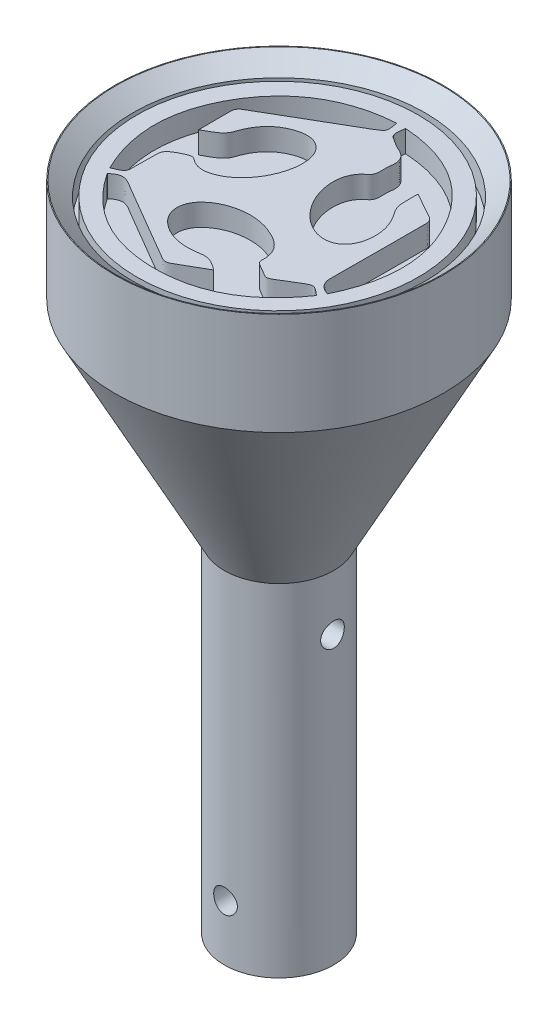
SolidWorks part; units mm, degrees
ref_plane "Piano frontale" through (0, 0, 0) normal (0, 0, 1) x (1, 0, 0)
ref_plane "Piano superiore" through (0, 0, 0) normal (0, 1, 0) x (1, 0, 0)
ref_plane "Piano destro" through (0, 0, 0) normal (1, 0, 0) x (0, 0, -1)
ref_plane "Piano1" through (0, 0, 0) normal (0, 0, -1) x (-1, 0, 0)
sketch "Schizzo1" plane through (0, 0, 0) normal (0, 0, -1) x (-1, 0, 0)
  line L0 (-22.5, 0) -> (0, 0)
  line L1 (0, 0) -> (0, 14.04)
  line L2 (0, 14.04) -> (-22.5, 14.04)
  line L3 (-22.5, 14.04) -> (-22.5, 0)
  line L4 (0, 0) -> (0, 14.04) construction
  line L5 (0, 19.9908) -> (0, -13.2342) construction
  dimension "D1" = 14.04
  dimension "D2" = 22.5
revolve "Rivoluzione1" add sketch "Schizzo1" angle 360 about L4
hole_wizard "Preforo Helicoil M39-1" positions "Schizzo3" profile "Schizzo2" hole size "M39x3.0" standard "Ansi Metric"
sketch "Schizzo3" plane through (0, 14.04, 0) normal (0, 1, 0) x (1, 0, 0)
  point P0 (0, 0)
sketch "Schizzo2" plane through (0, 14.04, 0) normal (1, 0, 0) x (0, 0, 1)
  line L0 (0, 0) -> (0, 5)
  line L1 (0, 5) -> (20, 5)
  line L2 (20, 5) -> (20, 2)
  line L3 (20, 2) -> (22.3835, 0)
  line L5 (22.3835, 0) -> (0, 0)
  line L6 (-20, 2) -> (-22.3835, 0) construction
  line L10 (0, 5) -> (-20, 5) construction
  line L11 (0, -6.35) -> (0, 107.95) construction
  dimension "Hole Dia." = 40
  dimension "Hole Depth" = 5
  dimension "Near C'Sink Dia." = 44.767
  dimension "Near C'Sink Angle" = 100
  dimension "Drill Angle" = 180
ref_plane "Piano2" through (0, 19, 0) normal (0, -1, 0) x (0, 0, 1)
sketch "Schizzo4" plane through (0, 19, 0) normal (0, -1, 0) x (0, 0, 1)
  circle A0 centre (-0.0209, 0.2088) radius 19.2566
extrude "Estrusione-Estrusione1" add sketch "Schizzo4" against normal blind 3 from surface at 9.96 starting at face at (0, 9.04, 20)
ref_plane "Piano3" through (0, 4.0001, 0) normal (0, 1, 0) x (1, 0, 0)
sketch "Schizzo5" plane through (0, 4.0001, 0) normal (0, 1, 0) x (1, 0, 0)
  arc A0 (-14.499, -9.0522) -> (-14.5293, -9.0002) centre (-13.9443, -8.6934) cw
  spline S0 degree 3 poles (-14.5293, -9.0002) (-14.5296, -8.9992) (-14.5303, -8.997) (-14.5301, -8.9936) (-14.53, -8.9903) (-14.5298, -8.987) (-14.5297, -8.9836) (-14.5296, -8.9803) (-14.5296, -8.977) (-14.5296, -8.9747) (-14.5296, -8.9736) knots 0 0 0 0 0.124119 0.24919 0.374331 0.499471 0.624605 0.749737 0.87487 1 1 1 1
  spline S1 degree 3 poles (-14.5296, -8.9736) (-14.4091, -8.8663) (-14.1681, -8.6517) (-13.7482, -8.4021) (-13.2752, -8.2701) (-12.782, -8.2936) (-12.3249, -8.4665) (-11.8982, -8.698) (-11.4855, -8.9555) (-11.0671, -9.2052) (-10.6494, -9.4559) (-10.2308, -9.7053) (-9.8118, -9.9539) (-9.3924, -10.2018) (-8.9725, -10.449) (-8.5523, -10.6956) (-8.1318, -10.9417) (-7.711, -11.1872) (-7.2899, -11.4324) (-6.8686, -11.6771) (-6.4472, -11.9216) (-6.0256, -12.1658) (-5.6039, -12.4099) (-5.1821, -12.6538) (-4.7604, -12.8977) (-4.3386, -13.1416) (-3.9168, -13.3856) (-3.4952, -13.6297) (-3.0737, -13.874) (-2.6523, -14.1186) (-2.2311, -14.3635) (-1.8102, -14.6089) (-1.3904, -14.8562) (-0.9688, -15.1) (-0.5569, -15.3548) (-0.0689, -15.4804) (0.4053, -15.3186) (0.8078, -15.0542) (1.2262, -14.8098) (1.6436, -14.5652) (2.0636, -14.3248) (2.4846, -14.0862) (2.9064, -13.8491) (3.3284, -13.6122) (3.7501, -13.375) (4.0305, -13.2155) (4.1707, -13.1358) knots 0 0 0 0 0.022617 0.045226 0.067918 0.090547 0.113217 0.135873 0.158666 0.181458 0.204249 0.227041 0.249832 0.272624 0.295415 0.318207 0.340998 0.36379 0.386582 0.409374 0.432166 0.454958 0.47775 0.500542 0.523334 0.546125 0.568917 0.591709 0.614501 0.637293 0.660084 0.682876 0.705668 0.72846 0.751198 0.773726 0.796268 0.818905 0.841546 0.864184 0.88682 0.909456 0.932092 0.954728 0.977364 1 1 1 1
  spline S2 degree 3 poles (4.1557, -13.1089) (4.1567, -13.1098) (4.1586, -13.1115) (4.1606, -13.1149) (4.1623, -13.1183) (4.1639, -13.1218) (4.1655, -13.1254) (4.1672, -13.1289) (4.1689, -13.1324) (4.1701, -13.1346) (4.1707, -13.1358) knots 0 0 0 0 0.124255 0.24931 0.374365 0.499494 0.624631 0.749743 0.874847 1 1 1 1
  spline S3 degree 3 poles (4.1557, -13.1089) (4.0758, -13.0505) (3.916, -12.9337) (3.6748, -12.7607) (3.4286, -12.5946) (3.1753, -12.4397) (2.9134, -12.3007) (2.6391, -12.1882) (2.3534, -12.1085) (2.0607, -12.0627) (1.7649, -12.0521) (1.4693, -12.0758) (1.1773, -12.1307) (0.8837, -12.1774) (0.5893, -12.2128) (0.295, -12.2384) (0.0007, -12.2535) (-0.2936, -12.2578) (-0.588, -12.2511) (-0.8825, -12.2328) (-1.177, -12.2027) (-1.4715, -12.1602) (-1.7651, -12.1047) (-2.0562, -12.036) (-2.3431, -11.954) (-2.6248, -11.8584) (-2.9011, -11.7494) (-3.172, -11.6266) (-3.4374, -11.4899) (-3.6964, -11.3394) (-3.9477, -11.1761) (-4.1902, -11.001) (-4.4235, -10.8147) (-4.6484, -10.6177) (-4.8598, -10.4046) (-5.0536, -10.1751) (-5.2273, -9.9306) (-5.3783, -9.6716) (-5.505, -9.3992) (-5.6056, -9.1162) (-5.6805, -8.8259) (-5.7285, -8.5299) (-5.7463, -8.2299) (-5.7328, -7.9298) (-5.6872, -7.6335) (-5.6109, -7.3431) (-5.5056, -7.0612) (-5.3743, -6.7899) (-5.2213, -6.5305) (-5.0478, -6.2844) (-4.8537, -6.0549) (-4.6429, -5.8413) (-4.4176, -5.6426) (-4.1813, -5.4572) (-3.9372, -5.2832) (-3.6863, -5.1213) (-3.4287, -4.9716) (-3.1644, -4.8341) (-2.8936, -4.7087) (-2.6162, -4.5955) (-2.3335, -4.4946) (-2.0469, -4.4063) (-1.7579, -4.3305) (-1.4669, -4.2669) (-1.1746, -4.2126) (-0.8806, -4.1683) (-0.5849, -4.1341) (-0.2873, -4.1105) (0.0119, -4.0979) (0.3117, -4.0965) (0.6109, -4.1065) (0.9087, -4.1282) (1.2045, -4.1611) (1.4984, -4.2052) (1.7904, -4.2604) (2.0803, -4.3266) (2.3681, -4.4036) (2.6539, -4.4914) (2.9369, -4.5896) (3.2164, -4.6974) (3.4914, -4.814) (3.7619, -4.9388) (4.0282, -5.0713) (4.2898, -5.2123) (4.5455, -5.3643) (4.7943, -5.5295) (5.0349, -5.7098) (5.2634, -5.9076) (5.4762, -6.1226) (5.6704, -6.3543) (5.8431, -6.6031) (5.9915, -6.8672) (6.1126, -7.1441) (6.2058, -7.4312) (6.2709, -7.7269) (6.3095, -8.0281) (6.3214, -8.3323) (6.3143, -8.6336) (6.3219, -8.9416) (6.4961, -9.2103) (6.7648, -9.3586) (7.0193, -9.5262) (7.2804, -9.6858) (7.5422, -9.8438) (7.8061, -9.9975) (8.0729, -10.1491) (8.3394, -10.2904) (8.6187, -10.4501) (8.9347, -10.3695) (9.2138, -10.2462) (9.4757, -10.0802) (9.7402, -9.923) (10.0034, -9.7627) (10.2667, -9.6028) (10.5298, -9.4424) (10.7929, -9.2821) (11.056, -9.1218) (11.3193, -8.9618) (11.5825, -8.8016) (11.847, -8.6437) (12.1105, -8.4843) (12.3848, -8.3456) (12.67, -8.225) (12.9912, -8.218) (13.1784, -8.3092) (13.2722, -8.3549) knots 0 0 0 0 0.008034 0.016066 0.024094 0.032131 0.040157 0.048136 0.056147 0.064169 0.072134 0.080116 0.08818 0.096235 0.10425 0.112237 0.120206 0.128165 0.136127 0.144102 0.152104 0.160152 0.168245 0.176346 0.184419 0.192454 0.200481 0.208519 0.216588 0.224706 0.232821 0.240902 0.248971 0.257047 0.265162 0.273305 0.2814 0.289478 0.297605 0.305745 0.313826 0.321906 0.330046 0.338175 0.34624 0.35434 0.362498 0.37063 0.378767 0.386921 0.39504 0.403136 0.411261 0.419402 0.427509 0.43558 0.443631 0.451682 0.459748 0.467849 0.47599 0.484107 0.492183 0.500234 0.508274 0.516313 0.52436 0.532431 0.540538 0.548658 0.556762 0.564834 0.572882 0.580918 0.588951 0.596991 0.605049 0.613133 0.621251 0.62936 0.637438 0.645494 0.653537 0.661572 0.669612 0.677676 0.685798 0.694 0.70218 0.710328 0.718508 0.726726 0.734875 0.743003 0.751188 0.759415 0.767621 0.775838 0.784009 0.792122 0.800376 0.808647 0.81692 0.825192 0.833464 0.841736 0.850004 0.858279 0.866593 0.874961 0.883297 0.891632 0.899968 0.908304 0.91664 0.924976 0.933312 0.941648 0.949984 0.95832 0.966656 0.974957 0.983279 0.991625 1 1 1 1
  spline S4 degree 3 poles (13.2722, -8.3549) (13.388, -8.4303) (13.62, -8.5811) (13.9371, -8.8499) (14.1486, -9.0284) (14.2545, -9.1177) knots 0 0 0 0 0.332682 0.666132 1 1 1 1
  spline S5 degree 3 poles (14.2545, -9.1177) (14.0751, -9.3707) (13.7168, -9.8757) (13.1489, -10.6091) (12.5516, -11.3159) (11.9228, -11.994) (11.2607, -12.6419) (10.564, -13.2573) (9.8348, -13.8352) (9.0763, -14.3698) (8.2925, -14.8573) (7.4839, -15.2967) (6.6502, -15.6874) (5.7912, -16.029) (4.9088, -16.3202) (4.0091, -16.5597) (3.0983, -16.7458) (2.1815, -16.8805) (1.2591, -16.9675) (0.3313, -17.0087) (-0.5993, -17.0045) (-1.5281, -16.9577) (-2.4505, -16.8661) (-3.3641, -16.7277) (-4.2688, -16.5403) (-5.1639, -16.3017) (-6.0473, -16.0107) (-6.9128, -15.6676) (-7.7537, -15.2745) (-8.5658, -14.8339) (-9.3491, -14.3467) (-10.104, -13.8139) (-10.8307, -13.2365) (-11.5268, -12.6178) (-12.1898, -11.9633) (-12.8179, -11.2775) (-13.4113, -10.5627) (-13.9747, -9.8223) (-14.324, -9.3092) (-14.499, -9.0522) knots 0 0 0 0 0.027124 0.054151 0.081105 0.108038 0.13501 0.162094 0.189308 0.216347 0.243214 0.269999 0.296795 0.323697 0.350803 0.378025 0.405083 0.432061 0.459039 0.486086 0.513259 0.540405 0.567396 0.594301 0.62119 0.64816 0.67528 0.702504 0.729535 0.756425 0.783272 0.810167 0.837198 0.864415 0.89158 0.918655 0.945713 0.972812 1 1 1 1
extrude "Taglio-Estrusione1" cut sketch "Schizzo5" against normal blind 3 from surface at 8.0399 starting at face at (-0.2088, 12.04, -19.2775)
ref_plane "Piano4" through (0, 4.0015, 0) normal (0, 1, 0) x (1, 0, 0)
sketch "Schizzo6" plane through (0, 4.0015, 0) normal (0, 1, 0) x (1, 0, 0)
  spline S0 degree 3 poles (9.1765, 9.8298) (9.1767, 9.8311) (9.1771, 9.8338) (9.179, 9.8374) (9.1811, 9.8409) (9.1833, 9.8442) (9.1856, 9.8476) (9.1878, 9.851) (9.1899, 9.8545) (9.1912, 9.8568) (9.1919, 9.858) knots 0 0 0 0 0.12437 0.249211 0.374335 0.499487 0.62465 0.749768 0.874894 1 1 1 1
  spline S1 degree 3 poles (9.1765, 9.8298) (9.1756, 9.7199) (9.1737, 9.5) (9.1712, 9.1702) (9.1687, 8.8403) (9.166, 8.5105) (9.163, 8.181) (9.1693, 7.8522) (9.1932, 7.5246) (9.2445, 7.1995) (9.3297, 6.8809) (9.4515, 6.5751) (9.6053, 6.2851) (9.7943, 6.0178) (9.9859, 5.7529) (10.1622, 5.4786) (10.3278, 5.1994) (10.4806, 4.9144) (10.6205, 4.6236) (10.7473, 4.3268) (10.8603, 4.0238) (10.9589, 3.7142) (11.0415, 3.3988) (11.1074, 3.0797) (11.1554, 2.759) (11.1857, 2.4378) (11.1982, 2.116) (11.1928, 1.7937) (11.1709, 1.4709) (11.1345, 1.1478) (11.0805, 0.8264) (11.0062, 0.5091) (10.9096, 0.1982) (10.7887, -0.1048) (10.643, -0.3971) (10.4718, -0.675) (10.2729, -0.9343) (10.0463, -1.1696) (9.7938, -1.3764) (9.5187, -1.5511) (9.2247, -1.693) (8.9163, -1.8017) (8.597, -1.8738) (8.2722, -1.9101) (7.9459, -1.9117) (7.6217, -1.8828) (7.3007, -1.8291) (6.9841, -1.752) (6.6743, -1.653) (6.3728, -1.533) (6.0798, -1.3942) (5.7949, -1.2384) (5.5183, -1.0676) (5.2503, -0.8844) (4.9913, -0.6901) (4.7418, -0.4851) (4.5017, -0.2698) (4.2709, -0.0441) (4.0494, 0.1916) (3.8371, 0.4371) (3.6345, 0.6913) (3.4422, 0.9531) (3.2601, 1.221) (3.088, 1.4948) (2.9253, 1.7742) (2.7723, 2.0593) (2.6296, 2.3505) (2.4979, 2.6476) (2.3781, 2.9497) (2.2707, 3.2559) (2.1762, 3.5654) (2.0949, 3.8779) (2.0264, 4.1935) (1.9714, 4.5123) (1.9306, 4.8342) (1.905, 5.1583) (1.8965, 5.4835) (1.9059, 5.8083) (1.9347, 6.132) (1.9825, 6.4538) (2.0517, 6.772) (2.1448, 7.0836) (2.2653, 7.3855) (2.4141, 7.6747) (2.5893, 7.9489) (2.7895, 8.2047) (3.0141, 8.4395) (3.2586, 8.6546) (3.5265, 8.8454) (3.7289, 9.1104) (3.8533, 9.4175) (3.9068, 9.7437) (3.9076, 10.073) (3.9043, 10.4023) (3.892, 10.7316) (3.8949, 11.062) (3.9424, 11.3887) (3.9811, 11.7155) (3.9846, 12.0448) (3.9402, 12.37) (3.8426, 12.6835) (3.6865, 12.9727) (3.4783, 13.2275) (3.23, 13.4429) (2.9547, 13.6202) (2.663, 13.7681) (2.3588, 13.8867) (2.0694, 14.038) (1.7921, 14.2082) (1.5138, 14.3769) (1.2365, 14.5473) (0.9626, 14.723) (0.697, 14.9111) (0.486, 15.1689) (0.4103, 15.4949) (0.4343, 15.8207) (0.4604, 16.1464) (0.4888, 16.4724) (0.5215, 16.6881) (0.5379, 16.7959) knots 0 0 0 0 0.008656 0.017313 0.025969 0.034626 0.043281 0.051913 0.060512 0.069122 0.077787 0.086422 0.09498 0.103565 0.112165 0.120721 0.129233 0.137712 0.146174 0.154635 0.163113 0.171629 0.180204 0.188771 0.197267 0.205722 0.214161 0.222609 0.231089 0.239622 0.248199 0.256739 0.265257 0.27381 0.282395 0.290938 0.299472 0.308068 0.316606 0.325105 0.333669 0.342251 0.350797 0.359381 0.367933 0.376443 0.384979 0.393534 0.402073 0.410568 0.419065 0.427582 0.436118 0.444648 0.453138 0.461604 0.470061 0.478524 0.487006 0.495522 0.504071 0.512593 0.521089 0.529571 0.538051 0.546537 0.555042 0.563578 0.572113 0.580626 0.589115 0.597582 0.606048 0.61453 0.623044 0.631587 0.640122 0.648644 0.657154 0.665694 0.674244 0.682769 0.691267 0.6998 0.708339 0.716848 0.725332 0.733878 0.742475 0.751097 0.759701 0.768326 0.776948 0.785599 0.794257 0.802897 0.811561 0.820215 0.828802 0.837408 0.845952 0.854513 0.863115 0.871718 0.880284 0.888835 0.897423 0.905966 0.914504 0.923043 0.931585 0.940125 0.948665 0.957169 0.965668 0.97425 0.98283 0.99141 1 1 1 1
  spline S2 degree 3 poles (0.5379, 16.7959) (0.8573, 16.7733) (1.4959, 16.728) (2.4461, 16.5993) (3.3867, 16.4325) (4.3138, 16.2186) (5.2264, 15.9571) (6.1239, 15.6455) (7.0057, 15.2819) (7.8669, 14.8649) (8.701, 14.3971) (9.5007, 13.8807) (10.2638, 13.3187) (10.9908, 12.7119) (11.6824, 12.061) (12.3382, 11.3678) (12.956, 10.6365) (13.5333, 9.8733) (14.0688, 9.0831) (14.5652, 8.2684) (15.0244, 7.4304) (15.4412, 6.5683) (15.8093, 5.6853) (16.1256, 4.7854) (16.3877, 3.8711) (16.594, 2.9421) (16.7439, 1.999) (16.8367, 1.0464) (16.8692, 0.0908) (16.8412, -0.8615) (16.7581, -1.8088) (16.6209, -2.7514) (16.4314, -3.6882) (16.192, -4.6153) (15.9074, -5.5293) (15.5802, -6.4276) (15.2178, -7.3134) (14.9425, -7.8893) (14.8046, -8.1776) knots 0 0 0 0 0.027963 0.055914 0.08372 0.111391 0.138997 0.166616 0.194342 0.22227 0.250161 0.27783 0.305376 0.332903 0.360509 0.38829 0.416227 0.444092 0.471847 0.499588 0.527398 0.555299 0.583197 0.61093 0.638578 0.666239 0.694015 0.721946 0.749804 0.777485 0.805124 0.832826 0.860657 0.88858 0.916433 0.94425 0.972087 1 1 1 1
  spline S3 degree 3 poles (14.8046, -8.1776) (14.6479, -8.1188) (14.3343, -8.0013) (13.903, -7.7399) (13.5399, -7.3879) (13.3008, -6.9412) (13.1895, -6.4492) (13.1767, -5.9469) (13.1914, -5.4455) (13.1964, -4.9434) (13.2042, -4.4415) (13.2105, -3.9395) (13.216, -3.4376) (13.2199, -2.9356) (13.2227, -2.4336) (13.2246, -1.9316) (13.2257, -1.4296) (13.2265, -0.9276) (13.227, -0.4257) (13.2272, 0.0763) (13.2273, 0.5783) (13.2272, 1.0803) (13.227, 1.5823) (13.2267, 2.0843) (13.2263, 2.5863) (13.2258, 3.0882) (13.2252, 3.5902) (13.2246, 4.0922) (13.224, 4.5942) (13.2235, 5.0962) (13.2226, 5.5982) (13.2232, 6.1001) (13.219, 6.6022) (13.243, 7.1004) (13.0902, 7.5986) (12.6859, 7.9174) (12.2393, 8.1326) (11.8022, 8.3775) (11.3642, 8.6187) (10.9291, 8.8655) (10.4952, 9.1143) (10.0613, 9.3631) (9.6292, 9.6152) (9.3377, 9.777) (9.1919, 9.858) knots 0 0 0 0 0.023832 0.047673 0.071397 0.095035 0.118813 0.142638 0.166501 0.190357 0.214214 0.238071 0.261927 0.285784 0.30964 0.333497 0.357354 0.38121 0.405067 0.428924 0.45278 0.476637 0.500494 0.52435 0.548207 0.572064 0.59592 0.619777 0.643634 0.66749 0.691347 0.715204 0.73906 0.762905 0.786329 0.809835 0.833602 0.857373 0.881144 0.904916 0.928687 0.952458 0.97623 1 1 1 1
extrude "Taglio-Estrusione2" cut sketch "Schizzo6" against normal blind 3 from surface at 8.0385 starting at face at (-0.2088, 12.04, -19.2775)
sketch "Schizzo7" plane through (0, 4.0001, 0) normal (0, 1, 0) x (1, 0, 0)
  spline S0 degree 3 poles (-13.4735, 2.4745) (-13.3829, 2.5211) (-13.2016, 2.6143) (-12.938, 2.7691) (-12.6728, 2.9208) (-12.4101, 3.0766) (-12.1487, 3.2346) (-11.8911, 3.3994) (-11.6416, 3.5762) (-11.4117, 3.7768) (-11.2095, 4.0038) (-11.0354, 4.2536) (-10.8901, 4.5242) (-10.7775, 4.8129) (-10.6851, 5.1095) (-10.5743, 5.3995) (-10.4542, 5.6842) (-10.3218, 5.9625) (-10.1768, 6.2342) (-10.0189, 6.4991) (-9.8477, 6.757) (-9.6631, 7.0077) (-9.4647, 7.25) (-9.2534, 7.4824) (-9.0304, 7.7029) (-8.7962, 7.9099) (-8.5515, 8.1032) (-8.2961, 8.283) (-8.0302, 8.4491) (-7.755, 8.6009) (-7.4722, 8.7379) (-7.1835, 8.8601) (-6.8897, 8.9678) (-6.5915, 9.0621) (-6.2886, 9.1432) (-5.9806, 9.208) (-5.6681, 9.2481) (-5.3534, 9.2567) (-5.0394, 9.2351) (-4.7289, 9.1829) (-4.4256, 9.0987) (-4.1335, 8.9817) (-3.856, 8.8328) (-3.5973, 8.6535) (-3.3603, 8.4463) (-3.1474, 8.214) (-2.9599, 7.9605) (-2.7989, 7.6892) (-2.6645, 7.4042) (-2.5558, 7.1089) (-2.4728, 6.8064) (-2.4134, 6.4985) (-2.377, 6.1865) (-2.356, 5.873) (-2.3491, 5.5595) (-2.3563, 5.247) (-2.377, 4.9356) (-2.4113, 4.6254) (-2.459, 4.3164) (-2.5198, 4.0085) (-2.5932, 3.7029) (-2.6785, 3.4007) (-2.7748, 3.103) (-2.8814, 2.8098) (-2.9976, 2.5209) (-3.1226, 2.2358) (-3.2569, 1.9549) (-3.4007, 1.6781) (-3.5544, 1.4056) (-3.7184, 1.138) (-3.8923, 0.8762) (-4.0755, 0.6215) (-4.2678, 0.3748) (-4.469, 0.1362) (-4.6791, -0.0943) (-4.8982, -0.3167) (-5.1265, -0.531) (-5.3644, -0.736) (-5.6117, -0.9304) (-5.8677, -1.1122) (-6.1321, -1.2801) (-6.4045, -1.4339) (-6.685, -1.5732) (-6.9737, -1.6975) (-7.2692, -1.8066) (-7.5702, -1.8994) (-7.877, -1.9702) (-8.1895, -2.0132) (-8.5051, -2.0246) (-8.8205, -2.0028) (-9.1315, -1.9462) (-9.4338, -1.8544) (-9.7214, -1.7246) (-9.9935, -1.5642) (-10.2509, -1.3838) (-10.4953, -1.1746) (-10.8186, -1.1269) (-11.1265, -1.1883) (-11.4062, -1.3236) (-11.6888, -1.4471) (-11.9662, -1.5828) (-12.2399, -1.7259) (-12.5081, -1.8792) (-12.7702, -2.042) (-13.0255, -2.2176) (-13.2363, -2.4474) (-13.3844, -2.7222) (-13.4569, -3.026) (-13.467, -3.3365) (-13.4669, -3.6471) (-13.4683, -3.9577) (-13.4686, -4.2683) (-13.4687, -4.5788) (-13.4688, -4.8894) (-13.4693, -5.2) (-13.4706, -5.5105) (-13.4733, -5.821) (-13.4769, -6.1314) (-13.4851, -6.4416) (-13.4863, -6.7522) (-13.522, -7.0631) (-13.6387, -7.366) (-13.8844, -7.5817) (-14.1625, -7.7385) (-14.4521, -7.8751) (-14.7469, -7.9989) (-14.9439, -8.0805) (-15.0425, -8.1213) knots 0 0 0 0 0.007834 0.015668 0.023501 0.031331 0.039159 0.046986 0.054841 0.062653 0.070396 0.078159 0.086017 0.093956 0.101949 0.1099 0.117816 0.125709 0.133595 0.14149 0.149413 0.157387 0.165424 0.173486 0.18153 0.189526 0.197507 0.205502 0.213534 0.221605 0.229656 0.237688 0.245703 0.25371 0.261734 0.269809 0.277894 0.285928 0.293978 0.302062 0.310101 0.318133 0.326213 0.334264 0.342287 0.35037 0.35845 0.366497 0.374588 0.38265 0.390662 0.398679 0.406741 0.414802 0.422835 0.430846 0.438837 0.446828 0.454836 0.462875 0.470951 0.479 0.487016 0.495009 0.502987 0.51096 0.518937 0.526928 0.534944 0.542995 0.551056 0.559102 0.567115 0.575109 0.583097 0.591091 0.599112 0.60717 0.615237 0.623287 0.631307 0.639315 0.647332 0.655381 0.663469 0.671544 0.679587 0.68766 0.695763 0.703832 0.711922 0.72002 0.728065 0.736129 0.744247 0.752338 0.760327 0.768309 0.776217 0.784128 0.792042 0.799956 0.807872 0.815793 0.823692 0.831617 0.839527 0.847432 0.855397 0.863365 0.871325 0.879285 0.887246 0.895207 0.903168 0.911128 0.919087 0.927045 0.935001 0.942956 0.950904 0.959028 0.967205 0.975409 0.983605 0.991801 1 1 1 1
  spline S1 degree 3 poles (-15.0425, -8.1213) (-15.1374, -7.93) (-15.3272, -7.5476) (-15.5847, -6.9611) (-15.8278, -6.3694) (-16.0515, -5.7715) (-16.2557, -5.1685) (-16.4394, -4.5605) (-16.6019, -3.9472) (-16.7427, -3.3286) (-16.8608, -2.7044) (-16.9556, -2.0744) (-17.0262, -1.4393) (-17.0723, -0.8019) (-17.0932, -0.1649) (-17.0874, 0.4698) (-17.0547, 1.1021) (-16.9959, 1.7317) (-16.912, 2.359) (-16.8028, 2.984) (-16.6676, 3.6065) (-16.5065, 4.2248) (-16.3197, 4.836) (-16.1087, 5.4378) (-15.8767, 6.03) (-15.6264, 6.614) (-15.3578, 7.1897) (-15.0698, 7.7569) (-14.7621, 8.3153) (-14.4348, 8.8639) (-14.0885, 9.4005) (-13.7246, 9.923) (-13.3439, 10.4304) (-12.9466, 10.9228) (-12.5326, 11.4001) (-12.1023, 11.8628) (-11.6535, 12.3089) (-11.1856, 12.7377) (-10.6982, 13.1487) (-10.1925, 13.5401) (-9.6713, 13.91) (-9.137, 14.2564) (-8.5911, 14.5794) (-8.0337, 14.8794) (-7.465, 15.157) (-6.8853, 15.4125) (-6.2948, 15.6466) (-5.6937, 15.8594) (-5.0837, 16.0508) (-4.4671, 16.2207) (-3.846, 16.3694) (-3.2213, 16.4975) (-2.5931, 16.6064) (-1.9614, 16.6946) (-1.3269, 16.7693) (-0.9018, 16.8009) (-0.689, 16.8167) knots 0 0 0 0 0.018637 0.037272 0.055905 0.074483 0.093001 0.111475 0.129927 0.148379 0.166854 0.185379 0.203992 0.222624 0.241163 0.25962 0.278027 0.296417 0.31482 0.333267 0.351793 0.370419 0.389036 0.407579 0.426078 0.444558 0.463038 0.481538 0.500081 0.518695 0.537302 0.555823 0.574272 0.592674 0.611051 0.629426 0.647826 0.666281 0.684824 0.703474 0.722096 0.740607 0.759051 0.777459 0.79586 0.814284 0.832757 0.851307 0.869942 0.888563 0.907138 0.925688 0.944232 0.962789 0.98137 1 1 1 1
  spline S2 degree 3 poles (-0.689, 16.8167) (-0.6611, 16.6674) (-0.6052, 16.3689) (-0.5479, 15.9206) (-0.4895, 15.4619) (-0.7038, 15.0316) (-1.0824, 14.7785) (-1.46, 14.5372) (-1.8504, 14.3127) (-2.2379, 14.084) (-2.6264, 13.8568) (-3.0149, 13.6296) (-3.4036, 13.4027) (-3.7924, 13.1761) (-4.1814, 12.9496) (-4.5704, 12.7233) (-4.9594, 12.497) (-5.3485, 12.2708) (-5.7376, 12.0446) (-6.1268, 11.8185) (-6.5159, 11.5924) (-6.9051, 11.3663) (-7.2943, 11.1402) (-7.6834, 10.9142) (-8.0726, 10.6881) (-8.4617, 10.462) (-8.8509, 10.2358) (-9.24, 10.0097) (-9.6291, 9.7836) (-10.0183, 9.5575) (-10.4074, 9.3313) (-10.7965, 9.1052) (-11.1857, 8.879) (-11.5747, 8.6528) (-11.9639, 8.4268) (-12.3527, 8.1998) (-12.7429, 7.9766) (-13.1279, 7.7425) (-13.42, 7.384) (-13.5106, 6.9346) (-13.4785, 6.4899) (-13.473, 6.0435) (-13.4739, 5.5973) (-13.4732, 5.1512) (-13.4732, 4.7051) (-13.4731, 4.259) (-13.4732, 3.8129) (-13.4733, 3.3667) (-13.4734, 2.9206) (-13.4735, 2.6232) (-13.4735, 2.4745) knots 0 0 0 0 0.021096 0.042193 0.063223 0.084023 0.104866 0.125706 0.146576 0.167447 0.188317 0.209188 0.230059 0.250929 0.2718 0.29267 0.313541 0.334412 0.355282 0.376153 0.397024 0.417894 0.438765 0.459635 0.480506 0.501377 0.522247 0.543118 0.563989 0.584859 0.60573 0.6266 0.647471 0.668342 0.689212 0.710083 0.730954 0.751825 0.772482 0.793102 0.813808 0.8345 0.855187 0.875875 0.896562 0.91725 0.937937 0.958625 0.979312 1 1 1 1
extrude "Taglio-Estrusione3" cut sketch "Schizzo7" against normal blind 3 from surface at 8.0399 starting at face at (8.4277, 12.04, -7.0765)
sketch "Schizzo9" plane through (0, 0, 0) normal (0, 0, 1) x (1, 0, 0)
  line L0 (0, 0) -> (22.5, 0)
  line L1 (22.5, 0) -> (7.5, -28.52)
  line L2 (7.5, -28.52) -> (0, -28.52)
  line L3 (0, 0) -> (0, -56.0573) construction
  line L4 (0, -28.52) -> (0, 0)
  dimension "D1" = 28.52
revolve "Rivoluzione2" add sketch "Schizzo9" angle 360 about L4
ref_plane "Piano5" through (0, -28.52, 0) normal (0, -1, 0) x (-1, 0, 0)
sketch "Schizzo17" plane through (0, -28.52, 0) normal (0, -1, 0) x (-1, 0, 0)
  circle A0 centre (0, 0) radius 7.5
extrude "Estrusione-Estrusione2" add sketch "Schizzo17" along normal blind 46.78
sketch "Schizzo18" plane through (0, 0, 0) normal (1, 0, 0) x (0, 0, -1)
  line L0 (-7.5, -28.52) -> (34.6016, -28.52) construction
  circle A0 centre (0, -36.11) radius 1.62
  dimension "D1" = 3.24
  dimension "D2" = 7.59
extrude "Taglio-Estrusione4" cut sketch "Schizzo18" against normal mid plane 30
sketch "Schizzo19" plane through (0, 0, 0) normal (0, 0, 1) x (1, 0, 0)
  line L0 (-3.4666, -28.52) -> (40.5801, -28.52) construction
  line L1 (7.5, -28.52) -> (-7.5, -28.52) construction
  circle A0 centre (0, -67.68) radius 1.62
  dimension "D1" = 3.24
  dimension "D2" = 39.16
extrude "Taglio-Estrusione5" cut sketch "Schizzo19" against normal mid plane 30
